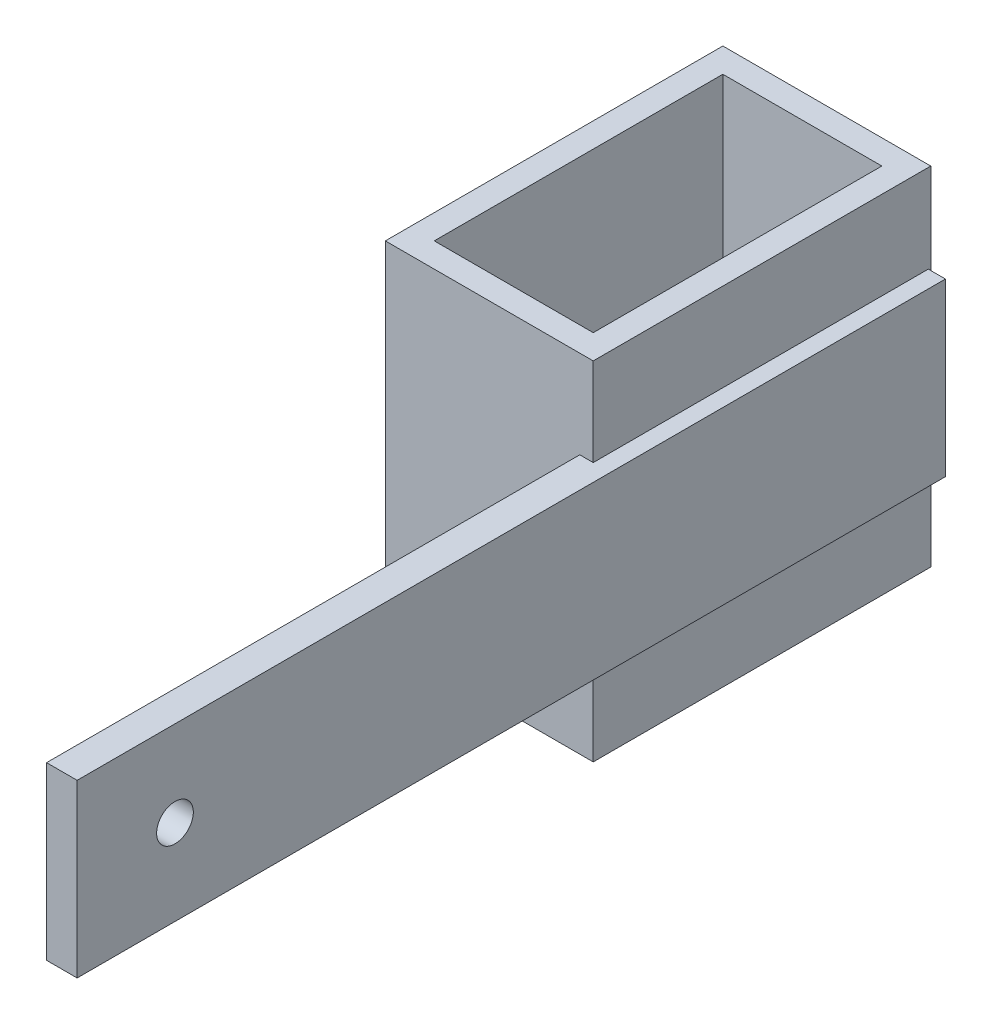
SolidWorks part; units mm, degrees
ref_plane "Front Plane" through (0, 0, 0) normal (0, 0, 1) x (1, 0, 0)
ref_plane "Top Plane" through (0, 0, 0) normal (0, 1, 0) x (1, 0, 0)
ref_plane "Right Plane" through (0, 0, 0) normal (1, 0, 0) x (0, 0, -1)
ref_plane "PZ_m63_000" through (0, 0, -63) normal (0, 0, 1) x (1, 0, 0)
sketch "S_box1" plane through (0, 0, -63) normal (0, 0, 1) x (1, 0, 0)
  line L0 (15.4, -7) -> (17.9, -7)
  line L1 (17.9, -7) -> (17.9, 7)
  line L2 (17.9, 7) -> (15.4, 7)
  line L3 (15.4, 7) -> (15.4, -7)
  dimension "P1" = 15.4
  dimension "P2" = 7
  dimension "P3" = 17.9
  dimension "P4" = 7
  dimension "P5" = 17.9
  dimension "P6" = 7
  dimension "P7" = 15.4
  dimension "P8" = 7
extrude "Boss_1" add sketch "S_box1" along normal blind 71
ref_plane "PZ_m63_200" through (0, 0, -63.2) normal (0, 0, 1) x (1, 0, 0)
sketch "S_box2" plane through (0, 0, -63.2) normal (0, 0, 1) x (1, 0, 0)
  line L0 (-0.5, -14.2) -> (16.5, -14.2)
  line L1 (16.5, -14.2) -> (16.5, 14.2)
  line L2 (16.5, 14.2) -> (-0.5, 14.2)
  line L3 (-0.5, 14.2) -> (-0.5, -14.2)
  dimension "P1" = 0.5
  dimension "P2" = 14.2
  dimension "P3" = 16.5
  dimension "P4" = 14.2
  dimension "P5" = 16.5
  dimension "P6" = 14.2
  dimension "P7" = 0.5
  dimension "P8" = 14.2
extrude "Boss_2" add sketch "S_box2" along normal blind 27.6
ref_plane "PZ_m61_200" through (0, 0, -61.2) normal (0, 0, 1) x (1, 0, 0)
sketch "S_cut3" plane through (0, 0, -61.2) normal (0, 0, 1) x (1, 0, 0)
  line L0 (1.5, -14.3) -> (14.5, -14.3)
  line L1 (14.5, -14.3) -> (14.5, 14.3)
  line L2 (14.5, 14.3) -> (1.5, 14.3)
  line L3 (1.5, 14.3) -> (1.5, -14.3)
  dimension "P1" = 1.5
  dimension "P2" = 14.3
  dimension "P3" = 14.5
  dimension "P4" = 14.3
  dimension "P5" = 14.5
  dimension "P6" = 14.3
  dimension "P7" = 1.5
  dimension "P8" = 14.3
extrude "Pocket_3" cut sketch "S_cut3" along normal blind 23.6
ref_plane "PX_p15_300" through (15.3, 0, 0) normal (1, 0, 0) x (0, 0, -1)
sketch "S_hole4" plane through (15.3, 0, 0) normal (1, 0, 0) x (0, 0, -1)
  circle A0 centre (0, 0) radius 1.5
  dimension "D1_S_hole4" = 3
extrude "Hole_4" cut sketch "S_hole4" along normal blind 2.7
equation "\"plate_t\" = 3"
equation "\"clearance\" = 0.4"
